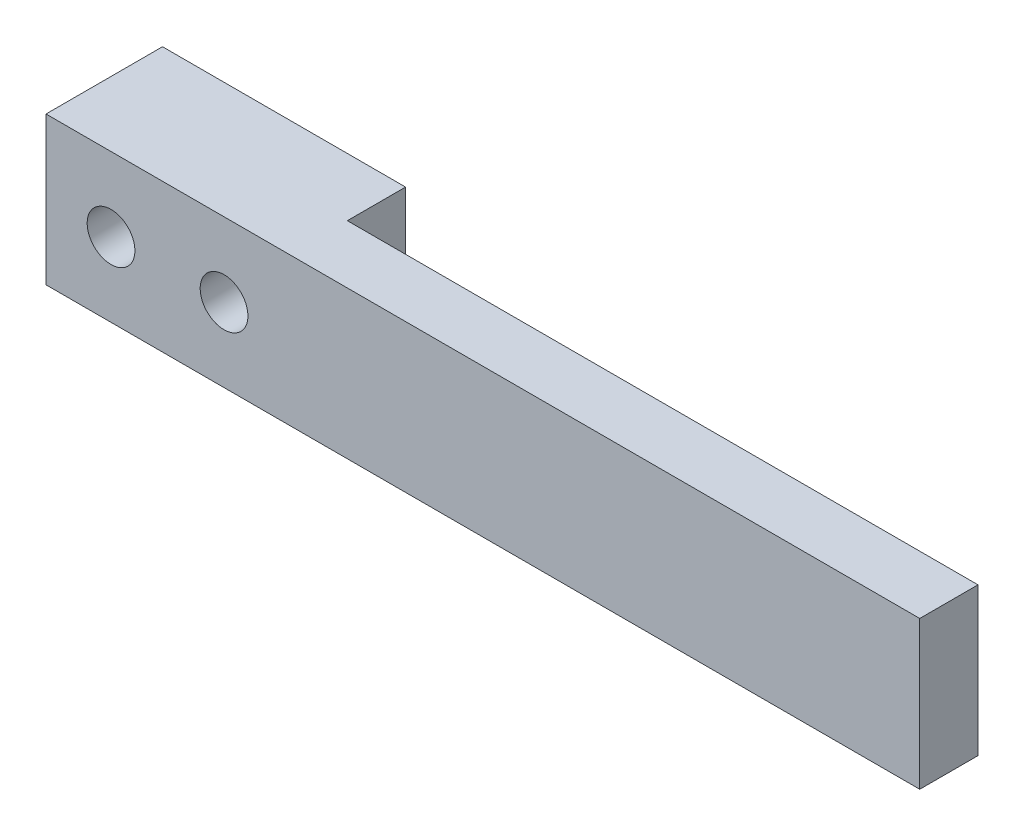
SolidWorks part; units mm, degrees
ref_plane "Front Plane" through (0, 0, 0) normal (0, 0, 1) x (1, 0, 0)
ref_plane "Top Plane" through (0, 0, 0) normal (0, 1, 0) x (1, 0, 0)
ref_plane "Right Plane" through (0, 0, 0) normal (1, 0, 0) x (0, 0, -1)
sketch "Sketch1" plane through (0, 0, 0) normal (0, 1, 0) x (1, 0, 0)
  line L0 (-58.5761, 0) -> (16.4239, 0)
  line L1 (16.4239, 0) -> (16.4239, 5)
  line L2 (16.4239, 5) -> (-37.7115, 5)
  line L3 (-37.7115, 5) -> (-37.7115, 10)
  line L4 (-58.5761, 0) -> (-58.5761, 10)
  line L5 (-58.5761, 10) -> (-37.7115, 10)
  dimension "D1" = 75
  dimension "D2" = 10
  dimension "D3" = 5
extrude "Boss-Extrude1" add sketch "Sketch1" along normal blind 12.7
sketch "Sketch2" plane through (0, 0, -10) normal (0, 0, -1) x (-1, 0, 0)
  line L0 (58.5761, 6.35) -> (37.7115, 6.35)
  line L1 (58.5761, 12.7) -> (58.5761, 0) construction
  line L2 (37.7115, 12.7) -> (37.7115, 0) construction
  line L3 (41.2438, 6.35) -> (41.2438, 0)
  line L4 (37.7115, 0) -> (58.5761, 0) construction
  line L5 (55.0438, 1.6197) -> (58.5761, 1.6197)
  line L6 (55.0438, 6.35) -> (55.0438, 0)
  line L7 (37.7115, 2.551) -> (41.2438, 2.551)
  line L8 (37.7115, 12.7) -> (37.7115, 0) construction
  circle A0 centre (43.2938, 6.35) radius 2.05
  circle A1 centre (52.9938, 6.35) radius 2.05
  dimension "D1" = 4.1
  dimension "D2" = 13.8
extrude "Cut-Extrude1" cut sketch "Sketch2" against normal blind 12.7 contours L0 A0 | L0 A0 | L0 A1 | L0 A1
